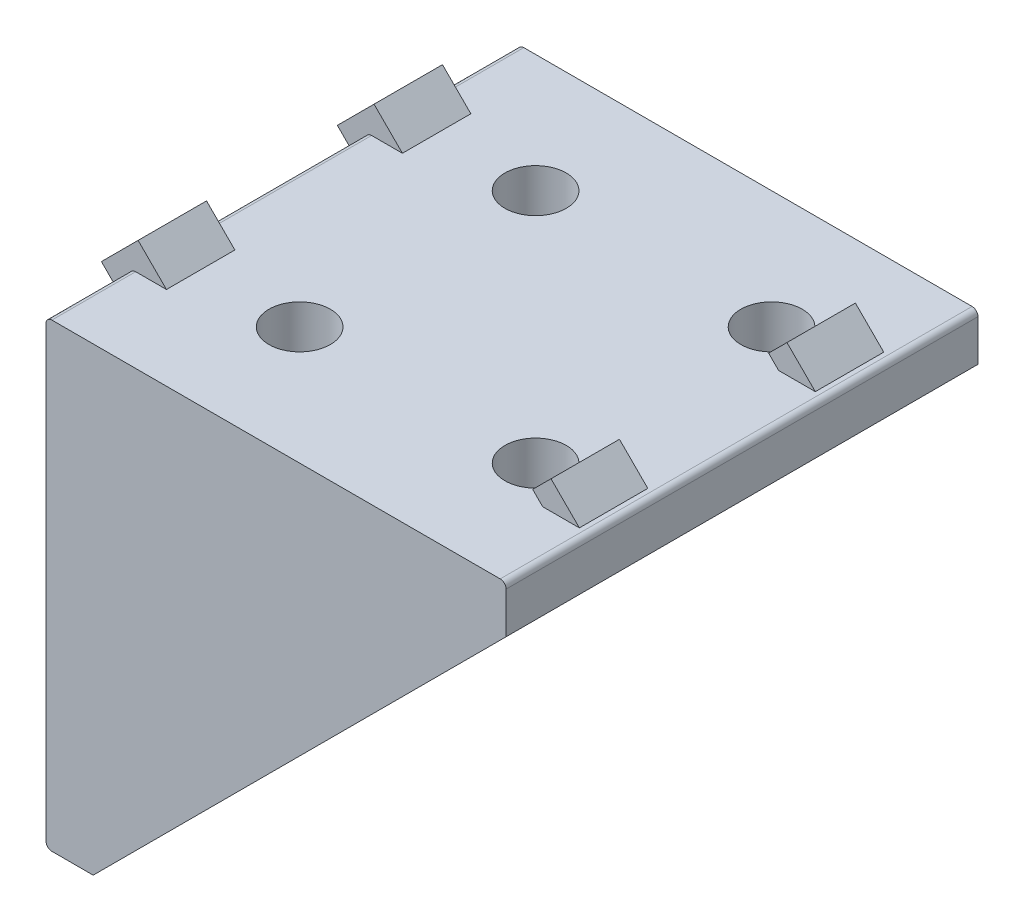
SolidWorks part; units mm, degrees
ref_plane "Спереди" through (0, 0, 0) normal (0, 0, 1) x (1, 0, 0)
ref_plane "Сверху" through (0, 0, 0) normal (0, 1, 0) x (1, 0, 0)
ref_plane "Справа" through (0, 0, 0) normal (1, 0, 0) x (0, 0, -1)
sketch "Эскиз1" plane through (0, 0, 0) normal (0, 0, 1) x (1, 0, 0)
  line L0 (0, 0) -> (0, -35)
  line L1 (0, -35) -> (-4, -35)
  line L2 (-4, -35) -> (-4, 4)
  line L3 (-4, 4) -> (35, 4)
  line L4 (35, 4) -> (35, 0)
  line L5 (35, 0) -> (0, 0)
  dimension "D1" = 39
  dimension "D2" = 39
  dimension "D3" = 4
  dimension "D4" = 4
extrude "Бобышка-Вытянуть1" add sketch "Эскиз1" along normal mid plane 40
sketch "Эскиз2" plane through (0, 0, 20) normal (0, 0, 1) x (1, 0, 0)
  line L0 (0, -35) -> (0, 0) construction
  line L1 (0, 0) -> (35, 0) construction
  line L2 (0, -35) -> (0, 0)
  line L3 (0, 0) -> (35, 0)
  line L4 (0, -35) -> (35, 0)
extrude "Бобышка-Вытянуть2" add sketch "Эскиз2" against normal blind 4
mirror "Зеркальное отражение1" about plane through (0, 0, 0) normal (0, 0, 1) of "Бобышка-Вытянуть2"
sketch "Эскиз3" plane through (0, 0, 0) normal (1, 0, 0) x (0, 0, -1)
  line L0 (-16, -35) -> (16, -35) construction
  line L1 (-20, 4) -> (-20, -35) construction
  line L2 (-10, -27.5) -> (10, -27.5) construction
  line L3 (-10, -27.5) -> (-10, -7.5) construction
  circle A0 centre (-10, -27.5) radius 2.6
  circle A1 centre (10, -27.5) radius 2.6
  circle A2 centre (10, -7.5) radius 2.6
  circle A3 centre (-10, -7.5) radius 2.6
  dimension "D1" = 5.2
  dimension "D3" = 10
  dimension "D4" = 2
  dimension "D2" = 7.5
  dimension "D6" = 90
  dimension "D7" = 20
  dimension "D8" = 20
  dimension "D5" = 2
extrude "Вырез-Вытянуть1" cut sketch "Эскиз3" against normal through all
sketch "Эскиз4" plane through (0, 0, 0) normal (0, -1, 0) x (1, 0, 0)
  line L0 (35, 16) -> (35, -16) construction
  line L1 (35, -20) -> (-4, -20) construction
  line L2 (27.5, -10) -> (7.5, -10) construction
  line L3 (27.5, -10) -> (27.5, 10) construction
  circle A0 centre (27.5, -10) radius 2.6
  circle A1 centre (7.5, -10) radius 2.6
  circle A2 centre (7.5, 10) radius 2.6
  circle A3 centre (27.5, 10) radius 2.6
  dimension "D1" = 5.2
  dimension "D2" = 7.5
  dimension "D3" = 10
  dimension "D6" = 90
  dimension "D7" = 20
  dimension "D8" = 20
  dimension "D4" = 2
  dimension "D5" = 2
extrude "Вырез-Вытянуть2" cut sketch "Эскиз4" against normal through all
sketch "Эскиз5" plane through (0, 0, 20) normal (0, 0, 1) x (1, 0, 0)
  line L0 (-0.8887, 4) -> (-3.2929, 6.4042)
  line L1 (35, 4) -> (-4, 4) construction
  line L2 (-3.2929, 6.4042) -> (-6.4042, 3.2929)
  line L3 (-6.4042, 3.2929) -> (-4, 0.8887)
  line L4 (-4, 4) -> (-4, -35) construction
  line L5 (-4, 0.8887) -> (-4, 4)
  line L6 (-4, 4) -> (-0.8887, 4)
  line L7 (35, 3.1113) -> (31.7071, 6.4042)
  line L8 (31.7071, 6.4042) -> (30.1515, 4.8485)
  line L9 (30.1515, 4.8485) -> (35, 0)
  line L10 (0, -35) -> (35, 0) construction
  line L12 (31.7071, 6.4042) -> (-3.2929, 6.4042) construction
  line L13 (35, 0) -> (35, 4) construction
  line L14 (35, 0) -> (35, 3.1113)
  line L15 (-1.2692, 1.2692) -> (35354.0698, -35354.0698) construction
  line L16 (-4.8485, -30.1515) -> (0, -35)
  line L17 (-6.4042, -31.7071) -> (-4.8485, -30.1515)
  line L18 (-3.1113, -35) -> (-6.4042, -31.7071)
  line L19 (0, -35) -> (-3.1113, -35)
  point P8 (31, 4)
  dimension "D1" = 45
  dimension "D2" = 4.4
  dimension "D3" = 2.2
  dimension "D4" = 1.2
  dimension "D5" = 2.2
  dimension "D6" = 1.2
  dimension "D7" = 2.4042
  dimension "D8" = 45
extrude "Бобышка-Вытянуть3" add sketch "Эскиз5" along normal mid plane 5.8 from offset 10 offset against normal yes
mirror "Зеркальное отражение2" about plane through (0, 0, 0) normal (0, 0, 1) of "Бобышка-Вытянуть3"
fillet "Скругление1" radius 0.5 5 edges at (-4, 4, -16.45) (-4, 4, 0) (-4, 4, 16.45) (-4, -35, 0) (35, 4, 0)
chamfer "Фаска1" distance 1 angle 45 5 edges at (0, -17.5, -16) (0, -17.5, 16) (17.5, 0, 16) (0, 0, 0) (17.5, 0, -16)
